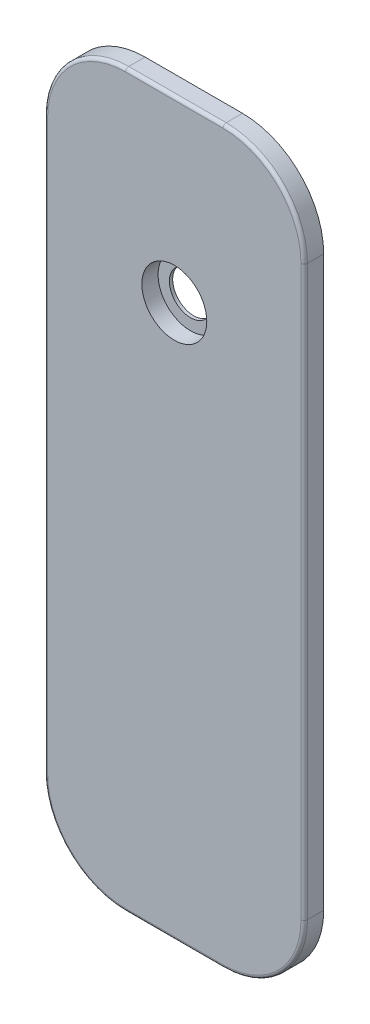
SolidWorks part; units mm, degrees
ref_plane "前视基准面" through (0, 0, 0) normal (0, 0, 1) x (1, 0, 0)
ref_plane "上视基准面" through (0, 0, 0) normal (0, 1, 0) x (1, 0, 0)
ref_plane "右视基准面" through (0, 0, 0) normal (1, 0, 0) x (0, 0, -1)
sketch "草图1" plane through (0, 0, 0) normal (0, 0, 1) x (1, 0, 0)
  line L0 (0, 112.5) -> (0, 0) construction
  line L1 (15, 112.5) -> (-15, 112.5)
  line L2 (40, 87.5) -> (40, -87.5)
  line L3 (15, -112.5) -> (-15, -112.5)
  line L4 (-40, 87.5) -> (-40, -87.5)
  arc A0 (-15, -112.5) -> (-40, -87.5) centre (-15, -87.5) cw
  arc A1 (40, -87.5) -> (15, -112.5) centre (15, -87.5) cw
  arc A2 (15, 112.5) -> (40, 87.5) centre (15, 87.5) cw
  arc A3 (-15, 112.5) -> (-40, 87.5) centre (-15, 87.5) ccw
  circle A4 centre (0, 57.5) radius 6.5
  point P4 (0, 112.5)
  point P6 (-40, 0)
  point P9 (-40, -112.5)
  point P14 (40, 112.5)
  point P17 (-40, 112.5)
  dimension "D3" = 25
  dimension "D4" = 13
  dimension "D1" = 80
  dimension "D2" = 225
  dimension "D5" = 55
extrude "凸台-拉伸1" add sketch "草图1" along normal blind 6
fillet "圆角1" radius 1 8 edges at (32.6777, -105.1777, 6) (0, -112.5, 6) (-32.6777, -105.1777, 6) (-40, 0, 6) (-32.6777, 105.1777, 6) (0, 112.5, 6) (32.6777, 105.1777, 6) (40, 0, 6)
sketch "草图2" plane through (0, 0, 6) normal (0, 0, 1) x (1, 0, 0)
  circle A0 centre (0, 57.5) radius 10
  dimension "D1" = 20
extrude "切除-拉伸1" cut sketch "草图2" against normal blind 5
